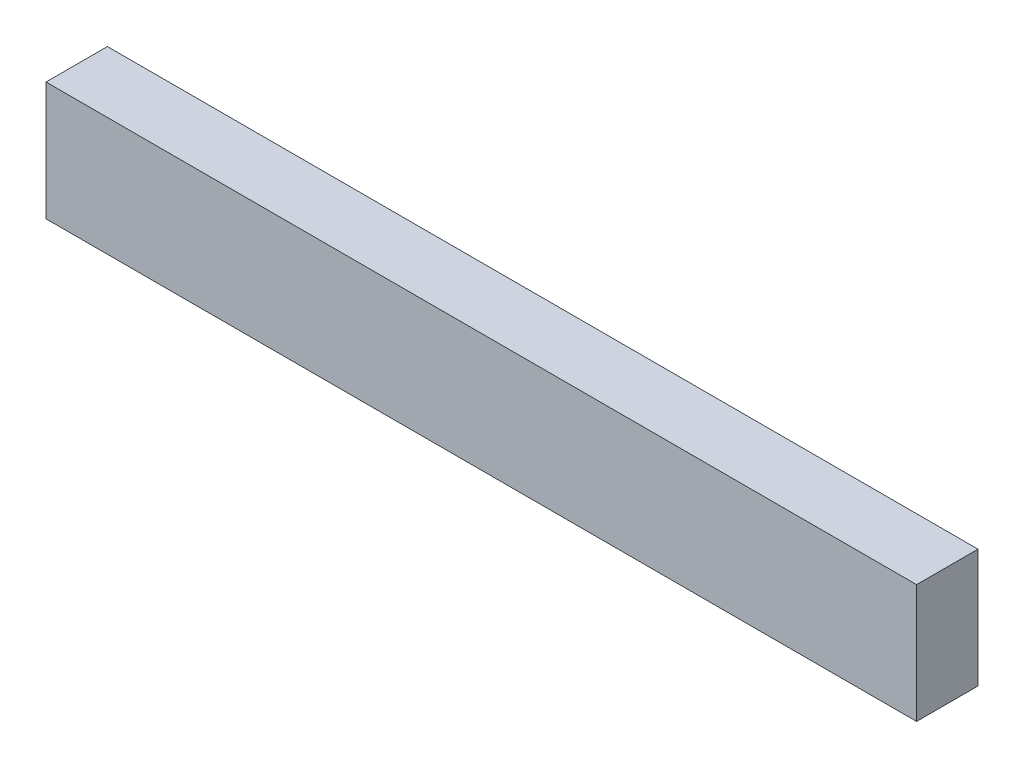
SolidWorks part; units mm, degrees
material "S-Glass Fiber"
ref_plane "Front Plane" through (0, 0, 0) normal (0, 0, 1) x (1, 0, 0)
ref_plane "Top Plane" through (0, 0, 0) normal (0, 1, 0) x (1, 0, 0)
ref_plane "Right Plane" through (0, 0, 0) normal (1, 0, 0) x (0, 0, -1)
sketch "Sketch1" plane through (0, 0, 0) normal (0, 1, 0) x (1, 0, 0)
  line L1 (-45, -3.175) -> (45, -3.175)
  line L2 (-45, -3.175) -> (-45, 3.175)
  line L3 (-45, 3.175) -> (45, 3.175)
  line L4 (45, -3.175) -> (45, 3.175)
  line L5 (-45, -3.175) -> (45, 3.175) construction
  line L6 (-45, 3.175) -> (45, -3.175) construction
  point P0 (0, 0)
extrude "Boss-Extrude1" add sketch "Sketch1" along normal blind 12.25
